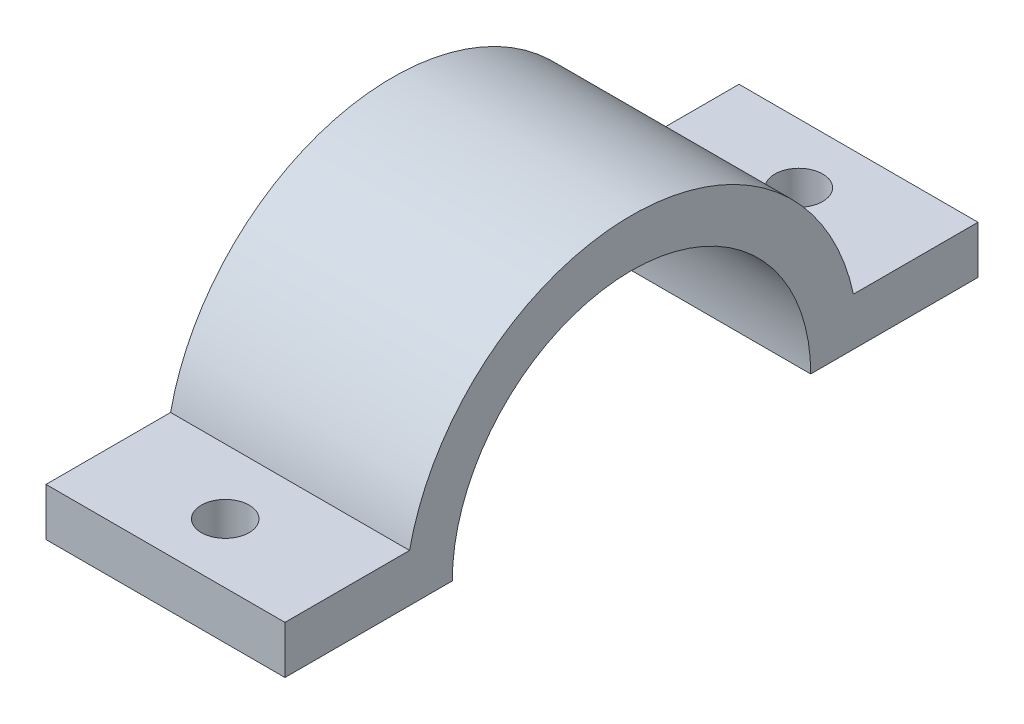
SolidWorks part; units mm, degrees
ref_plane "Front Plane" through (0, 0, 0) normal (0, 0, 1) x (1, 0, 0)
ref_plane "Top Plane" through (0, 0, 0) normal (0, 1, 0) x (1, 0, 0)
ref_plane "Right Plane" through (0, 0, 0) normal (1, 0, 0) x (0, 0, -1)
sketch "Sketch1" plane through (0, 0, 0) normal (1, 0, 0) x (0, 0, -1)
  line L0 (7.5, 0) -> (14.5, 0)
  line L1 (-7.5, 0) -> (-14.5, 0)
  line L2 (-14.5, 0) -> (-14.5, 2)
  line L3 (-14.5, 2) -> (-9.2871, 2)
  line L4 (14.5, 0) -> (14.5, 2)
  line L5 (14.5, 2) -> (9.2871, 2)
  arc A0 (-7.5, 0) -> (7.5, 0) centre (0, 0) cw
  arc A1 (-9.2871, 2) -> (9.2871, 2) centre (0, 0) cw
extrude "Boss-Extrude1" add sketch "Sketch1" along normal blind 10
sketch "Sketch2" plane through (0, 2, 0) normal (0, 1, 0) x (1, 0, 0)
  circle A0 centre (5, 12) radius 1
extrude "Cut-Extrude1" cut sketch "Sketch2" against normal blind 2
sketch "Sketch3" plane through (0, 0, 0) normal (0, 1, 0) x (1, 0, 0)
  circle A0 centre (5, -12) radius 1
extrude "Cut-Extrude5" cut sketch "Sketch3" along normal blind 2
